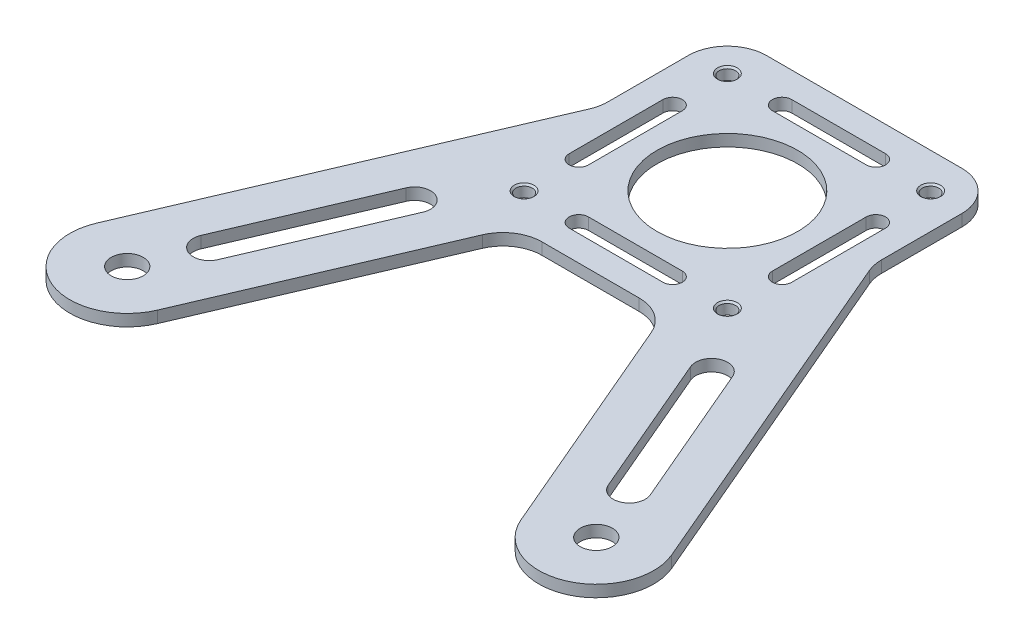
SolidWorks part; units mm, degrees
ref_plane "前视基准面" through (0, 0, 0) normal (0, 0, 1) x (1, 0, 0)
ref_plane "上视基准面" through (0, 0, 0) normal (0, 1, 0) x (1, 0, 0)
ref_plane "右视基准面" through (0, 0, 0) normal (1, 0, 0) x (0, 0, -1)
other "Configuration Table"
sketch "草图1" plane through (0, 0, 0) normal (0, 1, 0) x (1, 0, 0)
  line L0 (35, 0) -> (35, -70) construction
  line L5 (0, 0) -> (70, 0)
  line L6 (0, 0) -> (0, -32.5965)
  line L7 (15.9777, -70) -> (54.0223, -70)
  line L8 (70, 0) -> (70, -32.5965)
  line L9 (-25, -128.5244) -> (95, -128.5244) construction
  line L10 (13.5121, -75.772) -> (-11.4879, -134.2964)
  line L11 (83.5121, -64.228) -> (70, -32.5965)
  line L12 (-13.5121, -64.228) -> (-38.5121, -122.7524)
  line L13 (83.5121, -64.228) -> (108.5121, -122.7524)
  line L16 (-13.5121, -64.228) -> (0, -32.5965)
  line L17 (13.5121, -75.772) -> (15.9777, -70)
  line L18 (56.4879, -75.772) -> (81.4879, -134.2964)
  line L19 (56.4879, -75.772) -> (54.0223, -70)
  arc A1 (-38.5121, -122.7524) -> (-11.4879, -134.2964) centre (-25, -128.5244) ccw
  arc A2 (108.5121, -122.7524) -> (81.4879, -134.2964) centre (95, -128.5244) cw
  point P0 (0, 0)
  dimension "D1" = 70
  dimension "D2" = 120
  dimension "D3" = 180
  dimension "D4" = 180
  dimension "D5" = 128.5244
extrude "凸台-拉伸1" add sketch "草图1" along normal blind 3
sketch "草图2" plane through (0, 3, 0) normal (0, 1, 0) x (1, 0, 0)
  line L0 (9, -9) -> (61, -9) construction
  line L1 (70, 0) -> (0, 0) construction
  line L3 (0, 0) -> (0, -32.5965) construction
  circle A0 centre (9, -9) radius 2.5
  circle A1 centre (61, -9) radius 2.5
  circle A2 centre (61, -61) radius 2.5
  circle A3 centre (9, -61) radius 2.5
  point P5 (61, -9)
  point P6 (9, -9)
  point P11 (61, -61)
  point P13 (9, -61)
  dimension "D1" = 5
  dimension "D2" = 9
  dimension "D3" = 9
  dimension "D6" = 52
  dimension "D4" = 2
  dimension "D5" = 2
hole_wizard "M5 螺纹孔1" positions "草图2" profile "草图3" tap size "M5" standard "GB" end condition up to next
sketch "草图3" plane through (9, 3, 61) normal (1, 0, 0) x (0, 0, 1)
  line L0 (0, 0) -> (0, 3)
  line L1 (0, 3) -> (2.1, 3)
  line L2 (2.1, 3) -> (2.1, 0.425)
  line L3 (2.1, 0.425) -> (2.525, 0)
  line L5 (2.525, 0) -> (0, 0)
  line L6 (-2.1, 0.425) -> (-2.525, 0) construction
  line L11 (0, -6.35) -> (0, 107.95) construction
  dimension "通孔螺纹孔钻头直径" = 4.2
  dimension "通孔螺纹孔钻头深度" = 3
  dimension "近端锥形沉头孔直径" = 5.05
  dimension "近端锥形沉头孔角度" = 90
cosmetic thread "孔螺蚊线1" parameters "D2"=5
cosmetic thread "孔螺蚊线2" parameters "D2"=5
cosmetic thread "孔螺蚊线3" parameters "D2"=5
cosmetic thread "孔螺蚊线4" parameters "D2"=5
sketch "草图4" plane through (0, 3, 0) normal (0, 1, 0) x (1, 0, 0)
  circle A0 centre (-25, -128.5244) radius 4.1
  circle A1 centre (95, -128.5244) radius 4.1
  dimension "D1" = 8.2
  dimension "D2" = 8.2
  dimension "D3" = 120
extrude "切除-拉伸1" cut sketch "草图4" against normal up to next
fillet "圆角1" radius 10 6 edges at (54.0223, 1.5, 70) (15.9777, 1.5, 70) (0, 1.5, 32.5965) (70, 1.5, 32.5965) (70, 1.5, 0) (0, 1.5, 0)
sketch "草图5" plane through (0, 3, 0) normal (0, 1, 0) x (1, 0, 0)
  line L0 (9, -9) -> (61, -61) construction
  line L5 (9, -61) -> (61, -9) construction
  circle A0 centre (35, -35) radius 18
  dimension "D1" = 36
extrude "切除-拉伸2" cut sketch "草图5" against normal up to next
sketch "草图6" plane through (0, 3, 0) normal (0, 1, 0) x (1, 0, 0)
  line L0 (35, 0) -> (35, -50000) construction
  line L1 (60, 0) -> (10, 0) construction
  line L2 (22.5802, -70) -> (47.4198, -70) construction
  line L3 (-24.2016, -126.6554) -> (-4.5978, -80.7633) construction
  line L4 (-0.8039, -34.4784) -> (-38.5121, -122.7524) construction
  line L5 (-18.7147, -113.8106) -> (-3.0014, -77.0262) construction
  line L6 (-22.4851, -112.2) -> (-6.7718, -75.4156)
  line L7 (-14.9443, -115.4213) -> (0.769, -78.6368)
  line L8 (9, -9) -> (61, -9) construction
  line L9 (88.7147, -113.8106) -> (73.0014, -77.0262) construction
  line L10 (92.4851, -112.2) -> (76.7718, -75.4156)
  line L11 (84.9443, -115.4213) -> (69.231, -78.6368)
  line L12 (23, -9) -> (47, -9) construction
  line L13 (23, -6.5229) -> (47, -6.5229)
  line L14 (23, -11.4771) -> (47, -11.4771)
  line L15 (61, -23) -> (61, -47) construction
  line L16 (63.4771, -23) -> (63.4771, -47)
  line L17 (58.5229, -23) -> (58.5229, -47)
  line L18 (47, -61) -> (23, -61) construction
  line L19 (47, -63.4771) -> (23, -63.4771)
  line L20 (47, -58.5229) -> (23, -58.5229)
  line L21 (9, -47) -> (9, -23) construction
  line L22 (6.5229, -47) -> (6.5229, -23)
  line L23 (11.4771, -47) -> (11.4771, -23)
  arc A0 (-22.4851, -112.2) -> (-14.9443, -115.4213) centre (-18.7147, -113.8106) ccw
  arc A1 (0.769, -78.6368) -> (-6.7718, -75.4156) centre (-3.0014, -77.0262) ccw
  circle A2 centre (-25, -128.5244) radius 4.1 construction
  arc A3 (92.4851, -112.2) -> (84.9443, -115.4213) centre (88.7147, -113.8106) cw
  arc A4 (69.231, -78.6368) -> (76.7718, -75.4156) centre (73.0014, -77.0262) cw
  arc A5 (23, -6.5229) -> (23, -11.4771) centre (23, -9) ccw
  arc A6 (47, -11.4771) -> (47, -6.5229) centre (47, -9) ccw
  arc A7 (63.4771, -23) -> (58.5229, -23) centre (61, -23) ccw
  arc A8 (58.5229, -47) -> (63.4771, -47) centre (61, -47) ccw
  arc A9 (47, -63.4771) -> (47, -58.5229) centre (47, -61) ccw
  arc A10 (23, -58.5229) -> (23, -63.4771) centre (23, -61) ccw
  arc A11 (6.5229, -47) -> (11.4771, -47) centre (9, -47) ccw
  arc A12 (11.4771, -23) -> (6.5229, -23) centre (9, -23) ccw
  point P4 (35, 0)
  point P7 (35, -70)
  point P10 (-25, -128.5244)
  point P15 (-10.8581, -95.4184)
  point P24 (80.8581, -95.4184)
  point P36 (35, -9)
  point P41 (35, -35)
  point P48 (61, -35)
  point P53 (35, -35)
  point P56 (35, -61)
  point P61 (35, -35)
  point P64 (9, -35)
  point P69 (35, -35)
  point P70 (35, -35)
  dimension "D2" = 36
  dimension "D1" = 8.2
  dimension "D3" = 24
  dimension "D4" = 40
  dimension "D6" = 26
  dimension "D7" = 26
  dimension "D5" = 4
extrude "切除-拉伸3" cut sketch "草图6" against normal up to next
